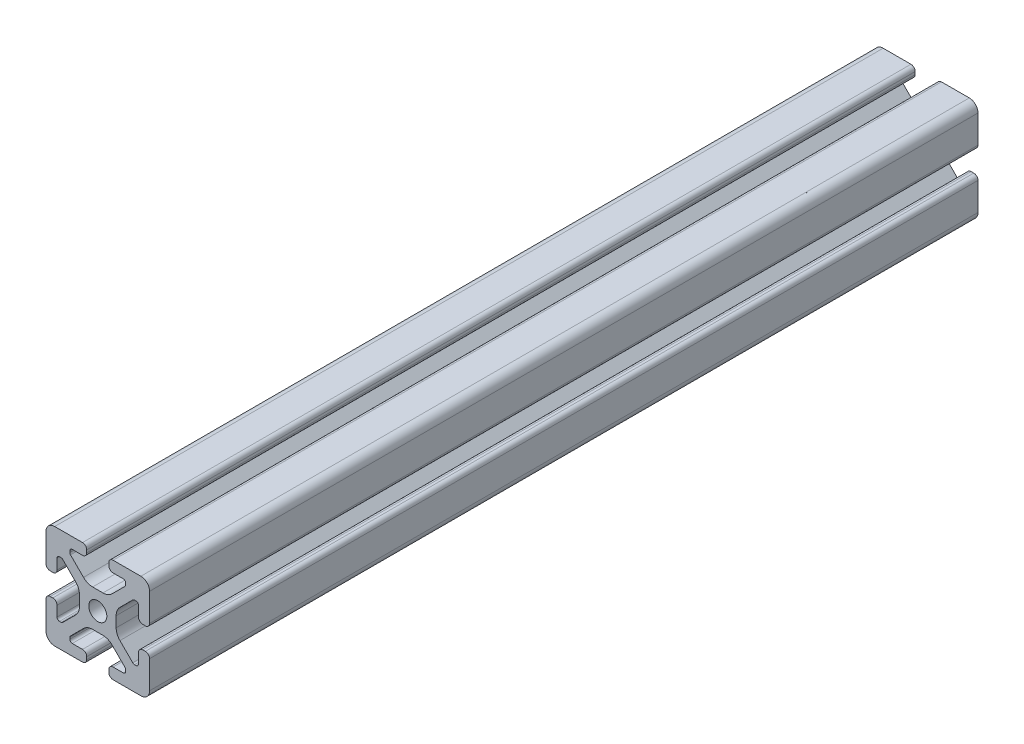
SolidWorks part; units mm, degrees
ref_plane "Front Plane" through (0, 0, 0) normal (0, 0, 1) x (1, 0, 0)
ref_plane "Top Plane" through (0, 0, 0) normal (0, 1, 0) x (1, 0, 0)
ref_plane "Right Plane" through (0, 0, 0) normal (1, 0, 0) x (0, 0, -1)
sketch "Sketch1" plane through (0, 0, 0) normal (0, 0, 1) x (1, 0, 0)
  line L0 (-4.064, 19.05) -> (-4.064, -19.05) construction
  line L1 (-19.05, -19.05) -> (19.05, -19.05) construction
  line L2 (-19.05, -19.05) -> (-19.05, 19.05) construction
  line L3 (-19.05, 19.05) -> (19.05, 19.05) construction
  line L4 (19.05, -19.05) -> (19.05, 19.05) construction
  line L5 (0, 19.05) -> (0, -19.05) construction
  line L6 (-19.05, 0) -> (19.05, 0) construction
  line L7 (-4.064, -19.05) -> (4.064, 19.05) construction
  line L8 (4.064, 19.05) -> (4.064, -19.05) construction
  circle A0 centre (0, 0) radius 3.3274
  point P0 (0, 0)
  line B0 (-10.287, 13.5524) -> (-10.287, 14.0843)
  line B1 (-9.3853, 14.986) -> (-5.6176, 14.986)
  line B2 (-4.064, 16.5396) -> (-4.064, 17.4964)
  line B3 (-5.6176, 19.05) -> (-7.9742, 19.05)
  line B4 (-9.4982, 19.05) -> (-14.3277, 19.05)
  line B5 (-19.05, 14.3277) -> (-19.05, 9.4961)
  line B6 (-19.05, 7.9763) -> (-19.05, 5.6176)
  line B7 (-17.4964, 4.064) -> (-16.5396, 4.064)
  line B8 (-14.986, 5.6176) -> (-14.986, 9.3853)
  line B9 (-14.0843, 10.287) -> (-13.516, 10.287)
  line B10 (-12.8784, 10.0229) -> (-8.1476, 5.2921)
  line B11 (-6.7564, 1.9335) -> (-6.7564, -1.9335)
  line B12 (-8.1476, -5.2921) -> (-12.8784, -10.0229)
  line B13 (-13.516, -10.287) -> (-14.0843, -10.287)
  line B14 (-14.986, -9.3853) -> (-14.986, -5.6176)
  line B15 (-16.5396, -4.064) -> (-17.4964, -4.064)
  line B16 (-19.05, -5.6176) -> (-19.05, -7.9763)
  line B17 (-19.05, -9.4961) -> (-19.05, -14.3277)
  line B18 (-14.3277, -19.05) -> (-9.4961, -19.05)
  line B19 (-7.9763, -19.05) -> (-5.6176, -19.05)
  line B20 (-4.064, -17.4964) -> (-4.064, -16.5396)
  line B21 (-5.6176, -14.986) -> (-9.3853, -14.986)
  line B22 (-10.287, -14.0843) -> (-10.287, -13.5524)
  line B23 (-10.0229, -12.9148) -> (-5.2522, -8.144)
  line B24 (-1.9022, -6.7564) -> (1.9022, -6.7564)
  line B25 (5.2522, -8.144) -> (10.0229, -12.9148)
  line B26 (10.287, -13.5524) -> (10.287, -14.0843)
  line B27 (9.3853, -14.986) -> (5.6176, -14.986)
  line B28 (4.064, -16.5396) -> (4.064, -17.4964)
  line B29 (5.6176, -19.05) -> (7.9763, -19.05)
  line B30 (9.4961, -19.05) -> (14.3277, -19.05)
  line B31 (19.05, -14.3277) -> (19.05, -9.4961)
  line B32 (19.05, -7.9763) -> (19.05, -5.6176)
  line B33 (17.4964, -4.064) -> (16.5396, -4.064)
  line B34 (14.986, -5.6176) -> (14.986, -9.3853)
  line B35 (14.0843, -10.287) -> (13.516, -10.287)
  line B36 (12.8784, -10.0229) -> (8.1476, -5.2921)
  line B37 (6.7564, -1.9335) -> (6.7564, 1.9335)
  line B38 (8.1476, 5.2921) -> (12.8784, 10.0229)
  line B39 (13.516, 10.287) -> (14.0843, 10.287)
  line B40 (14.986, 9.3853) -> (14.986, 5.6176)
  line B41 (16.5396, 4.064) -> (17.4964, 4.064)
  line B42 (19.05, 5.6176) -> (19.05, 7.9763)
  line B43 (19.05, 9.4961) -> (19.05, 14.3277)
  line B44 (14.3277, 19.05) -> (9.4982, 19.05)
  line B45 (7.9742, 19.05) -> (5.6176, 19.05)
  line B46 (4.064, 17.4964) -> (4.064, 16.5396)
  line B47 (5.6176, 14.986) -> (9.3853, 14.986)
  line B48 (10.287, 14.0843) -> (10.287, 13.5524)
  line B49 (10.0229, 12.9148) -> (5.2522, 8.144)
  line B50 (1.9022, 6.7564) -> (-1.9022, 6.7564)
  line B51 (-5.2522, 8.144) -> (-10.0229, 12.9148)
  circle B52 centre (0, 0) radius 3.3274
  arc B53 (-5.6176, 14.986) -> (-4.064, 16.5396) centre (-5.6176, 16.5396) ccw
  arc B54 (-4.064, 17.4964) -> (-5.6176, 19.05) centre (-5.6176, 17.4964) ccw
  arc B55 (-9.4982, 19.05) -> (-7.9742, 19.05) centre (-8.7362, 19.05) ccw
  arc B56 (-15.8475, 19.05) -> (-14.3277, 19.05) centre (-15.0876, 18.9933) ccw
  arc B57 (-15.8475, 19.05) -> (-19.05, 15.8475) centre (-15.8751, 15.8751) ccw
  arc B58 (-19.05, 14.3277) -> (-19.05, 15.8475) centre (-18.9933, 15.0876) ccw
  arc B59 (-19.05, 7.9763) -> (-19.05, 9.4961) centre (-18.9933, 8.7362) ccw
  arc B60 (-19.05, 5.6176) -> (-17.4964, 4.064) centre (-17.4964, 5.6176) ccw
  arc B61 (-16.5396, 4.064) -> (-14.986, 5.6176) centre (-16.5396, 5.6176) ccw
  arc B62 (-14.0843, 10.287) -> (-14.986, 9.3853) centre (-14.0843, 9.3853) ccw
  arc B63 (-12.8784, 10.0229) -> (-13.516, 10.287) centre (-13.516, 9.3853) ccw
  arc B64 (-6.7564, 1.9335) -> (-8.1476, 5.2921) centre (-11.5062, 1.9335) ccw
  arc B65 (-8.1476, -5.2921) -> (-6.7564, -1.9335) centre (-11.5062, -1.9335) ccw
  arc B66 (-13.516, -10.287) -> (-12.8784, -10.0229) centre (-13.516, -9.3853) ccw
  arc B67 (-14.986, -9.3853) -> (-14.0843, -10.287) centre (-14.0843, -9.3853) ccw
  arc B68 (-14.986, -5.6176) -> (-16.5396, -4.064) centre (-16.5396, -5.6176) ccw
  arc B69 (-17.4964, -4.064) -> (-19.05, -5.6176) centre (-17.4964, -5.6176) ccw
  arc B70 (-19.05, -9.4961) -> (-19.05, -7.9763) centre (-18.9933, -8.7362) ccw
  arc B71 (-19.05, -15.8475) -> (-19.05, -14.3277) centre (-18.9933, -15.0876) ccw
  arc B72 (-19.05, -15.8475) -> (-15.8475, -19.05) centre (-15.8751, -15.8751) ccw
  arc B73 (-14.3277, -19.05) -> (-15.8475, -19.05) centre (-15.0876, -18.9933) ccw
  arc B74 (-7.9763, -19.05) -> (-9.4961, -19.05) centre (-8.7362, -18.9933) ccw
  arc B75 (-5.6176, -19.05) -> (-4.064, -17.4964) centre (-5.6176, -17.4964) ccw
  arc B76 (-4.064, -16.5396) -> (-5.6176, -14.986) centre (-5.6176, -16.5396) ccw
  arc B77 (-10.287, -14.0843) -> (-9.3853, -14.986) centre (-9.3853, -14.0843) ccw
  arc B78 (-10.0229, -12.9148) -> (-10.287, -13.5524) centre (-9.3853, -13.5524) ccw
  arc B79 (-1.9022, -6.7564) -> (-5.2522, -8.144) centre (-1.9022, -11.494) ccw
  arc B80 (5.2522, -8.144) -> (1.9022, -6.7564) centre (1.9022, -11.494) ccw
  arc B81 (10.287, -13.5524) -> (10.0229, -12.9148) centre (9.3853, -13.5524) ccw
  arc B82 (9.3853, -14.986) -> (10.287, -14.0843) centre (9.3853, -14.0843) ccw
  arc B83 (5.6176, -14.986) -> (4.064, -16.5396) centre (5.6176, -16.5396) ccw
  arc B84 (4.064, -17.4964) -> (5.6176, -19.05) centre (5.6176, -17.4964) ccw
  arc B85 (9.4961, -19.05) -> (7.9763, -19.05) centre (8.7362, -18.9933) ccw
  arc B86 (15.8475, -19.05) -> (14.3277, -19.05) centre (15.0876, -18.9933) ccw
  arc B87 (15.8475, -19.05) -> (19.05, -15.8475) centre (15.8751, -15.8751) ccw
  arc B88 (19.05, -14.3277) -> (19.05, -15.8475) centre (18.9933, -15.0876) ccw
  arc B89 (19.05, -7.9763) -> (19.05, -9.4961) centre (18.9933, -8.7362) ccw
  arc B90 (19.05, -5.6176) -> (17.4964, -4.064) centre (17.4964, -5.6176) ccw
  arc B91 (16.5396, -4.064) -> (14.986, -5.6176) centre (16.5396, -5.6176) ccw
  arc B92 (14.0843, -10.287) -> (14.986, -9.3853) centre (14.0843, -9.3853) ccw
  arc B93 (12.8784, -10.0229) -> (13.516, -10.287) centre (13.516, -9.3853) ccw
  arc B94 (6.7564, -1.9335) -> (8.1476, -5.2921) centre (11.5062, -1.9335) ccw
  arc B95 (8.1476, 5.2921) -> (6.7564, 1.9335) centre (11.5062, 1.9335) ccw
  arc B96 (13.516, 10.287) -> (12.8784, 10.0229) centre (13.516, 9.3853) ccw
  arc B97 (14.986, 9.3853) -> (14.0843, 10.287) centre (14.0843, 9.3853) ccw
  arc B98 (14.986, 5.6176) -> (16.5396, 4.064) centre (16.5396, 5.6176) ccw
  arc B99 (17.4964, 4.064) -> (19.05, 5.6176) centre (17.4964, 5.6176) ccw
  arc B100 (19.05, 9.4961) -> (19.05, 7.9763) centre (18.9933, 8.7362) ccw
  arc B101 (19.05, 15.8475) -> (19.05, 14.3277) centre (18.9933, 15.0876) ccw
  arc B102 (19.05, 15.8475) -> (15.8475, 19.05) centre (15.8751, 15.8751) ccw
  arc B103 (14.3277, 19.05) -> (15.8475, 19.05) centre (15.0876, 18.9933) ccw
  arc B104 (7.9742, 19.05) -> (9.4982, 19.05) centre (8.7362, 19.05) ccw
  arc B105 (5.6176, 19.05) -> (4.064, 17.4964) centre (5.6176, 17.4964) ccw
  arc B106 (4.064, 16.5396) -> (5.6176, 14.986) centre (5.6176, 16.5396) ccw
  arc B107 (10.287, 14.0843) -> (9.3853, 14.986) centre (9.3853, 14.0843) ccw
  arc B108 (10.0229, 12.9148) -> (10.287, 13.5524) centre (9.3853, 13.5524) ccw
  arc B109 (1.9022, 6.7564) -> (5.2522, 8.144) centre (1.9022, 11.494) ccw
  arc B110 (-5.2522, 8.144) -> (-1.9022, 6.7564) centre (-1.9022, 11.494) ccw
  arc B111 (-10.287, 13.5524) -> (-10.0229, 12.9148) centre (-9.3853, 13.5524) ccw
  dimension "Center Hole Diameter" = 6.6548
  dimension "Rail Width" = 38.1
  dimension "Rail Height" = 38.1
  dimension "T-Slot Width" = 8.128
  dimension "T-Slot Depth" = 12.2936
sketch_block_instance "Block1-1"
sketch_block "Block1"
sketch "Sketch2" plane through (0, 0, 0) normal (1, 0, 0) x (0, 0, -1)
  line L0 (-152.4, 0) -> (152.4, 0) construction
  line L1 (-101.6, 0) -> (-101.6, 19.05) construction
  line L2 (-101.6, 19.05) -> (101.6, 19.05) construction
  line L3 (101.6, 19.05) -> (101.6, 0) construction
  line L4 (-25, 19.05) -> (25, 19.05) construction
  line L6 (3045, -19.05) -> (-3045, -19.05) construction
  line L7 (0, 19.05) -> (0, -19.05) construction
  point P14 (-100.35, 19.05)
  dimension "D1" = 50.8
  dimension "Length Range [Min]" = 50
  dimension "Length Range [Max]" = 6090
  dimension "Rep Length" = 304.8
  dimension "Length Increment" = 2.5
sketch "Sketch3" plane through (0, 0, 0) normal (0, 0, 1) x (1, 0, 0)
  line L0 (-4.064, 16.5396) -> (-4.064, 17.4964) construction
  line L1 (-9.3853, 14.986) -> (-5.6176, 14.986) construction
  line L2 (-10.287, 13.5524) -> (-10.287, 14.0843) construction
  line L3 (-5.2522, 8.144) -> (-10.0229, 12.9148) construction
  line L4 (1.9022, 6.7564) -> (-1.9022, 6.7564) construction
  line L5 (10.0229, 12.9148) -> (5.2522, 8.144) construction
  line L6 (10.287, 14.0843) -> (10.287, 13.5524) construction
  line L7 (5.6176, 14.986) -> (9.3853, 14.986) construction
  line L8 (4.064, 17.4964) -> (4.064, 16.5396) construction
  line L9 (7.9742, 19.05) -> (5.6176, 19.05) construction
  line L10 (14.3277, 19.05) -> (9.4982, 19.05) construction
  line L11 (19.05, 9.4961) -> (19.05, 14.3277) construction
  line L12 (19.05, 5.6176) -> (19.05, 7.9763) construction
  line L13 (16.5396, 4.064) -> (17.4964, 4.064) construction
  line L14 (14.986, 9.3853) -> (14.986, 5.6176) construction
  line L15 (13.516, 10.287) -> (14.0843, 10.287) construction
  line L16 (8.1476, 5.2921) -> (12.8784, 10.0229) construction
  line L17 (6.7564, -1.9335) -> (6.7564, 1.9335) construction
  line L18 (12.8784, -10.0229) -> (8.1476, -5.2921) construction
  line L19 (14.0843, -10.287) -> (13.516, -10.287) construction
  line L20 (14.986, -5.6176) -> (14.986, -9.3853) construction
  line L21 (17.4964, -4.064) -> (16.5396, -4.064) construction
  line L22 (19.05, -7.9763) -> (19.05, -5.6176) construction
  line L23 (19.05, -14.3277) -> (19.05, -9.4961) construction
  line L24 (9.4961, -19.05) -> (14.3277, -19.05) construction
  line L25 (5.6176, -19.05) -> (7.9763, -19.05) construction
  line L26 (4.064, -16.5396) -> (4.064, -17.4964) construction
  line L27 (9.3853, -14.986) -> (5.6176, -14.986) construction
  line L28 (10.287, -13.5524) -> (10.287, -14.0843) construction
  line L29 (5.2522, -8.144) -> (10.0229, -12.9148) construction
  line L30 (-1.9022, -6.7564) -> (1.9022, -6.7564) construction
  line L31 (-10.0229, -12.9148) -> (-5.2522, -8.144) construction
  line L32 (-10.287, -14.0843) -> (-10.287, -13.5524) construction
  line L33 (-5.6176, -14.986) -> (-9.3853, -14.986) construction
  line L34 (-4.064, -17.4964) -> (-4.064, -16.5396) construction
  line L35 (-7.9763, -19.05) -> (-5.6176, -19.05) construction
  line L36 (-14.3277, -19.05) -> (-9.4961, -19.05) construction
  line L37 (-19.05, -9.4961) -> (-19.05, -14.3277) construction
  line L38 (-19.05, -5.6176) -> (-19.05, -7.9763) construction
  line L39 (-16.5396, -4.064) -> (-17.4964, -4.064) construction
  line L40 (-14.986, -9.3853) -> (-14.986, -5.6176) construction
  line L41 (-13.516, -10.287) -> (-14.0843, -10.287) construction
  line L42 (-8.1476, -5.2921) -> (-12.8784, -10.0229) construction
  line L43 (-6.7564, 1.9335) -> (-6.7564, -1.9335) construction
  line L44 (-12.8784, 10.0229) -> (-8.1476, 5.2921) construction
  line L45 (-14.0843, 10.287) -> (-13.516, 10.287) construction
  line L46 (-14.986, 5.6176) -> (-14.986, 9.3853) construction
  line L47 (-17.4964, 4.064) -> (-16.5396, 4.064) construction
  line L48 (-19.05, 7.9763) -> (-19.05, 5.6176) construction
  line L49 (-19.05, 14.3277) -> (-19.05, 9.4961) construction
  line L50 (-9.4982, 19.05) -> (-14.3277, 19.05) construction
  line L51 (-5.6176, 19.05) -> (-7.9742, 19.05) construction
  line L52 (-4.064, 16.5396) -> (-4.064, 17.4964)
  line L53 (-9.3853, 14.986) -> (-5.6176, 14.986)
  line L54 (-10.287, 13.5524) -> (-10.287, 14.0843)
  line L55 (-5.2522, 8.144) -> (-10.0229, 12.9148)
  line L56 (1.9022, 6.7564) -> (-1.9022, 6.7564)
  line L57 (10.0229, 12.9148) -> (5.2522, 8.144)
  line L58 (10.287, 14.0843) -> (10.287, 13.5524)
  line L59 (5.6176, 14.986) -> (9.3853, 14.986)
  line L60 (4.064, 17.4964) -> (4.064, 16.5396)
  line L61 (7.9742, 19.05) -> (5.6176, 19.05)
  line L62 (14.3277, 19.05) -> (9.4982, 19.05)
  line L63 (19.05, 9.4961) -> (19.05, 14.3277)
  line L64 (19.05, 5.6176) -> (19.05, 7.9763)
  line L65 (16.5396, 4.064) -> (17.4964, 4.064)
  line L66 (14.986, 9.3853) -> (14.986, 5.6176)
  line L67 (13.516, 10.287) -> (14.0843, 10.287)
  line L68 (8.1476, 5.2921) -> (12.8784, 10.0229)
  line L69 (6.7564, -1.9335) -> (6.7564, 1.9335)
  line L70 (12.8784, -10.0229) -> (8.1476, -5.2921)
  line L71 (14.0843, -10.287) -> (13.516, -10.287)
  line L72 (14.986, -5.6176) -> (14.986, -9.3853)
  line L73 (17.4964, -4.064) -> (16.5396, -4.064)
  line L74 (19.05, -7.9763) -> (19.05, -5.6176)
  line L75 (19.05, -14.3277) -> (19.05, -9.4961)
  line L76 (9.4961, -19.05) -> (14.3277, -19.05)
  line L77 (5.6176, -19.05) -> (7.9763, -19.05)
  line L78 (4.064, -16.5396) -> (4.064, -17.4964)
  line L79 (9.3853, -14.986) -> (5.6176, -14.986)
  line L80 (10.287, -13.5524) -> (10.287, -14.0843)
  line L81 (5.2522, -8.144) -> (10.0229, -12.9148)
  line L82 (-1.9022, -6.7564) -> (1.9022, -6.7564)
  line L83 (-10.0229, -12.9148) -> (-5.2522, -8.144)
  line L84 (-10.287, -14.0843) -> (-10.287, -13.5524)
  line L85 (-5.6176, -14.986) -> (-9.3853, -14.986)
  line L86 (-4.064, -17.4964) -> (-4.064, -16.5396)
  line L87 (-7.9763, -19.05) -> (-5.6176, -19.05)
  line L88 (-14.3277, -19.05) -> (-9.4961, -19.05)
  line L89 (-19.05, -9.4961) -> (-19.05, -14.3277)
  line L90 (-19.05, -5.6176) -> (-19.05, -7.9763)
  line L91 (-16.5396, -4.064) -> (-17.4964, -4.064)
  line L92 (-14.986, -9.3853) -> (-14.986, -5.6176)
  line L93 (-13.516, -10.287) -> (-14.0843, -10.287)
  line L94 (-8.1476, -5.2921) -> (-12.8784, -10.0229)
  line L95 (-6.7564, 1.9335) -> (-6.7564, -1.9335)
  line L96 (-12.8784, 10.0229) -> (-8.1476, 5.2921)
  line L97 (-14.0843, 10.287) -> (-13.516, 10.287)
  line L98 (-14.986, 5.6176) -> (-14.986, 9.3853)
  line L99 (-17.4964, 4.064) -> (-16.5396, 4.064)
  line L100 (-19.05, 7.9763) -> (-19.05, 5.6176)
  line L101 (-19.05, 14.3277) -> (-19.05, 9.4961)
  line L102 (-9.4982, 19.05) -> (-14.3277, 19.05)
  line L103 (-5.6176, 19.05) -> (-7.9742, 19.05)
  line L104 (-7.9742, 19.05) -> (-9.4982, 19.05)
  line L105 (-14.3277, 19.05) -> (-15.8475, 19.05)
  line L106 (-19.05, 15.8475) -> (-19.05, 14.3277)
  line L107 (-19.05, 9.4961) -> (-19.05, 7.9763)
  line L108 (-19.05, -7.9763) -> (-19.05, -9.4961)
  line L109 (-19.05, -14.3277) -> (-19.05, -15.8475)
  line L110 (-15.8475, -19.05) -> (-14.3277, -19.05)
  line L111 (-9.4961, -19.05) -> (-7.9763, -19.05)
  line L112 (7.9763, -19.05) -> (9.4961, -19.05)
  line L113 (14.3277, -19.05) -> (15.8475, -19.05)
  line L114 (19.05, -15.8475) -> (19.05, -14.3277)
  line L115 (19.05, -9.4961) -> (19.05, -7.9763)
  line L116 (19.05, 7.9763) -> (19.05, 9.4961)
  line L117 (19.05, 14.3277) -> (19.05, 15.8475)
  line L118 (15.8475, 19.05) -> (14.3277, 19.05)
  line L119 (9.4982, 19.05) -> (7.9742, 19.05)
  circle A0 centre (0, 0) radius 3.3274 construction
  circle A1 centre (0, 0) radius 3.3274
  circle A2 centre (0, 0) radius 3.3274
  arc A3 (-5.6176, 14.986) -> (-4.064, 16.5396) centre (-5.6176, 16.5396) ccw construction
  arc A4 (-9.3853, 14.986) -> (-10.287, 14.0843) centre (-9.3853, 14.0843) ccw construction
  arc A5 (-10.287, 13.5524) -> (-10.0229, 12.9148) centre (-9.3853, 13.5524) ccw construction
  arc A6 (-5.2522, 8.144) -> (-1.9022, 6.7564) centre (-1.9022, 11.494) ccw construction
  arc A7 (1.9022, 6.7564) -> (5.2522, 8.144) centre (1.9022, 11.494) ccw construction
  arc A8 (10.0229, 12.9148) -> (10.287, 13.5524) centre (9.3853, 13.5524) ccw construction
  arc A9 (10.287, 14.0843) -> (9.3853, 14.986) centre (9.3853, 14.0843) ccw construction
  arc A10 (4.064, 16.5396) -> (5.6176, 14.986) centre (5.6176, 16.5396) ccw construction
  arc A11 (5.6176, 19.05) -> (4.064, 17.4964) centre (5.6176, 17.4964) ccw construction
  arc A14 (19.05, 15.8475) -> (15.8475, 19.05) centre (15.8751, 15.8751) ccw construction
  arc A17 (17.4964, 4.064) -> (19.05, 5.6176) centre (17.4964, 5.6176) ccw construction
  arc A18 (14.986, 5.6176) -> (16.5396, 4.064) centre (16.5396, 5.6176) ccw construction
  arc A19 (14.986, 9.3853) -> (14.0843, 10.287) centre (14.0843, 9.3853) ccw construction
  arc A20 (13.516, 10.287) -> (12.8784, 10.0229) centre (13.516, 9.3853) ccw construction
  arc A21 (8.1476, 5.2921) -> (6.7564, 1.9335) centre (11.5062, 1.9335) ccw construction
  arc A22 (6.7564, -1.9335) -> (8.1476, -5.2921) centre (11.5062, -1.9335) ccw construction
  arc A23 (12.8784, -10.0229) -> (13.516, -10.287) centre (13.516, -9.3853) ccw construction
  arc A24 (14.0843, -10.287) -> (14.986, -9.3853) centre (14.0843, -9.3853) ccw construction
  arc A25 (16.5396, -4.064) -> (14.986, -5.6176) centre (16.5396, -5.6176) ccw construction
  arc A26 (19.05, -5.6176) -> (17.4964, -4.064) centre (17.4964, -5.6176) ccw construction
  arc A29 (15.8475, -19.05) -> (19.05, -15.8475) centre (15.8751, -15.8751) ccw construction
  arc A32 (4.064, -17.4964) -> (5.6176, -19.05) centre (5.6176, -17.4964) ccw construction
  arc A33 (5.6176, -14.986) -> (4.064, -16.5396) centre (5.6176, -16.5396) ccw construction
  arc A34 (9.3853, -14.986) -> (10.287, -14.0843) centre (9.3853, -14.0843) ccw construction
  arc A35 (10.287, -13.5524) -> (10.0229, -12.9148) centre (9.3853, -13.5524) ccw construction
  arc A36 (5.2522, -8.144) -> (1.9022, -6.7564) centre (1.9022, -11.494) ccw construction
  arc A37 (-1.9022, -6.7564) -> (-5.2522, -8.144) centre (-1.9022, -11.494) ccw construction
  arc A38 (-10.0229, -12.9148) -> (-10.287, -13.5524) centre (-9.3853, -13.5524) ccw construction
  arc A39 (-10.287, -14.0843) -> (-9.3853, -14.986) centre (-9.3853, -14.0843) ccw construction
  arc A40 (-4.064, -16.5396) -> (-5.6176, -14.986) centre (-5.6176, -16.5396) ccw construction
  arc A41 (-5.6176, -19.05) -> (-4.064, -17.4964) centre (-5.6176, -17.4964) ccw construction
  arc A44 (-19.05, -15.8475) -> (-15.8475, -19.05) centre (-15.8751, -15.8751) ccw construction
  arc A47 (-17.4964, -4.064) -> (-19.05, -5.6176) centre (-17.4964, -5.6176) ccw construction
  arc A48 (-14.986, -5.6176) -> (-16.5396, -4.064) centre (-16.5396, -5.6176) ccw construction
  arc A49 (-14.986, -9.3853) -> (-14.0843, -10.287) centre (-14.0843, -9.3853) ccw construction
  arc A50 (-13.516, -10.287) -> (-12.8784, -10.0229) centre (-13.516, -9.3853) ccw construction
  arc A51 (-8.1476, -5.2921) -> (-6.7564, -1.9335) centre (-11.5062, -1.9335) ccw construction
  arc A52 (-6.7564, 1.9335) -> (-8.1476, 5.2921) centre (-11.5062, 1.9335) ccw construction
  arc A53 (-12.8784, 10.0229) -> (-13.516, 10.287) centre (-13.516, 9.3853) ccw construction
  arc A54 (-14.0843, 10.287) -> (-14.986, 9.3853) centre (-14.0843, 9.3853) ccw construction
  arc A55 (-16.5396, 4.064) -> (-14.986, 5.6176) centre (-16.5396, 5.6176) ccw construction
  arc A56 (-19.05, 5.6176) -> (-17.4964, 4.064) centre (-17.4964, 5.6176) ccw construction
  arc A59 (-15.8475, 19.05) -> (-19.05, 15.8475) centre (-15.8751, 15.8751) ccw construction
  arc A62 (-4.064, 17.4964) -> (-5.6176, 19.05) centre (-5.6176, 17.4964) ccw construction
  circle A63 centre (0, 0) radius 3.3274
  arc A64 (-5.6176, 14.986) -> (-4.064, 16.5396) centre (-5.6176, 16.5396) ccw
  arc A65 (-9.3853, 14.986) -> (-10.287, 14.0843) centre (-9.3853, 14.0843) ccw
  arc A66 (-10.287, 13.5524) -> (-10.0229, 12.9148) centre (-9.3853, 13.5524) ccw
  arc A67 (-5.2522, 8.144) -> (-1.9022, 6.7564) centre (-1.9022, 11.494) ccw
  arc A68 (1.9022, 6.7564) -> (5.2522, 8.144) centre (1.9022, 11.494) ccw
  arc A69 (10.0229, 12.9148) -> (10.287, 13.5524) centre (9.3853, 13.5524) ccw
  arc A70 (10.287, 14.0843) -> (9.3853, 14.986) centre (9.3853, 14.0843) ccw
  arc A71 (4.064, 16.5396) -> (5.6176, 14.986) centre (5.6176, 16.5396) ccw
  arc A72 (5.6176, 19.05) -> (4.064, 17.4964) centre (5.6176, 17.4964) ccw
  arc A75 (19.05, 15.8475) -> (15.8475, 19.05) centre (15.8751, 15.8751) ccw
  arc A78 (17.4964, 4.064) -> (19.05, 5.6176) centre (17.4964, 5.6176) ccw
  arc A79 (14.986, 5.6176) -> (16.5396, 4.064) centre (16.5396, 5.6176) ccw
  arc A80 (14.986, 9.3853) -> (14.0843, 10.287) centre (14.0843, 9.3853) ccw
  arc A81 (13.516, 10.287) -> (12.8784, 10.0229) centre (13.516, 9.3853) ccw
  arc A82 (8.1476, 5.2921) -> (6.7564, 1.9335) centre (11.5062, 1.9335) ccw
  arc A83 (6.7564, -1.9335) -> (8.1476, -5.2921) centre (11.5062, -1.9335) ccw
  arc A84 (12.8784, -10.0229) -> (13.516, -10.287) centre (13.516, -9.3853) ccw
  arc A85 (14.0843, -10.287) -> (14.986, -9.3853) centre (14.0843, -9.3853) ccw
  arc A86 (16.5396, -4.064) -> (14.986, -5.6176) centre (16.5396, -5.6176) ccw
  arc A87 (19.05, -5.6176) -> (17.4964, -4.064) centre (17.4964, -5.6176) ccw
  arc A90 (15.8475, -19.05) -> (19.05, -15.8475) centre (15.8751, -15.8751) ccw
  arc A93 (4.064, -17.4964) -> (5.6176, -19.05) centre (5.6176, -17.4964) ccw
  arc A94 (5.6176, -14.986) -> (4.064, -16.5396) centre (5.6176, -16.5396) ccw
  arc A95 (9.3853, -14.986) -> (10.287, -14.0843) centre (9.3853, -14.0843) ccw
  arc A96 (10.287, -13.5524) -> (10.0229, -12.9148) centre (9.3853, -13.5524) ccw
  arc A97 (5.2522, -8.144) -> (1.9022, -6.7564) centre (1.9022, -11.494) ccw
  arc A98 (-1.9022, -6.7564) -> (-5.2522, -8.144) centre (-1.9022, -11.494) ccw
  arc A99 (-10.0229, -12.9148) -> (-10.287, -13.5524) centre (-9.3853, -13.5524) ccw
  arc A100 (-10.287, -14.0843) -> (-9.3853, -14.986) centre (-9.3853, -14.0843) ccw
  arc A101 (-4.064, -16.5396) -> (-5.6176, -14.986) centre (-5.6176, -16.5396) ccw
  arc A102 (-5.6176, -19.05) -> (-4.064, -17.4964) centre (-5.6176, -17.4964) ccw
  arc A105 (-19.05, -15.8475) -> (-15.8475, -19.05) centre (-15.8751, -15.8751) ccw
  arc A108 (-17.4964, -4.064) -> (-19.05, -5.6176) centre (-17.4964, -5.6176) ccw
  arc A109 (-14.986, -5.6176) -> (-16.5396, -4.064) centre (-16.5396, -5.6176) ccw
  arc A110 (-14.986, -9.3853) -> (-14.0843, -10.287) centre (-14.0843, -9.3853) ccw
  arc A111 (-13.516, -10.287) -> (-12.8784, -10.0229) centre (-13.516, -9.3853) ccw
  arc A112 (-8.1476, -5.2921) -> (-6.7564, -1.9335) centre (-11.5062, -1.9335) ccw
  arc A113 (-6.7564, 1.9335) -> (-8.1476, 5.2921) centre (-11.5062, 1.9335) ccw
  arc A114 (-12.8784, 10.0229) -> (-13.516, 10.287) centre (-13.516, 9.3853) ccw
  arc A115 (-14.0843, 10.287) -> (-14.986, 9.3853) centre (-14.0843, 9.3853) ccw
  arc A116 (-16.5396, 4.064) -> (-14.986, 5.6176) centre (-16.5396, 5.6176) ccw
  arc A117 (-19.05, 5.6176) -> (-17.4964, 4.064) centre (-17.4964, 5.6176) ccw
  arc A120 (-15.8475, 19.05) -> (-19.05, 15.8475) centre (-15.8751, 15.8751) ccw
  arc A123 (-4.064, 17.4964) -> (-5.6176, 19.05) centre (-5.6176, 17.4964) ccw
  dimension "D1" = 0
extrude "Boss-Extrude1" add sketch "Sketch3" along normal up to vertex (152.4 mm away) and the other way up to vertex (152.4 mm away)
